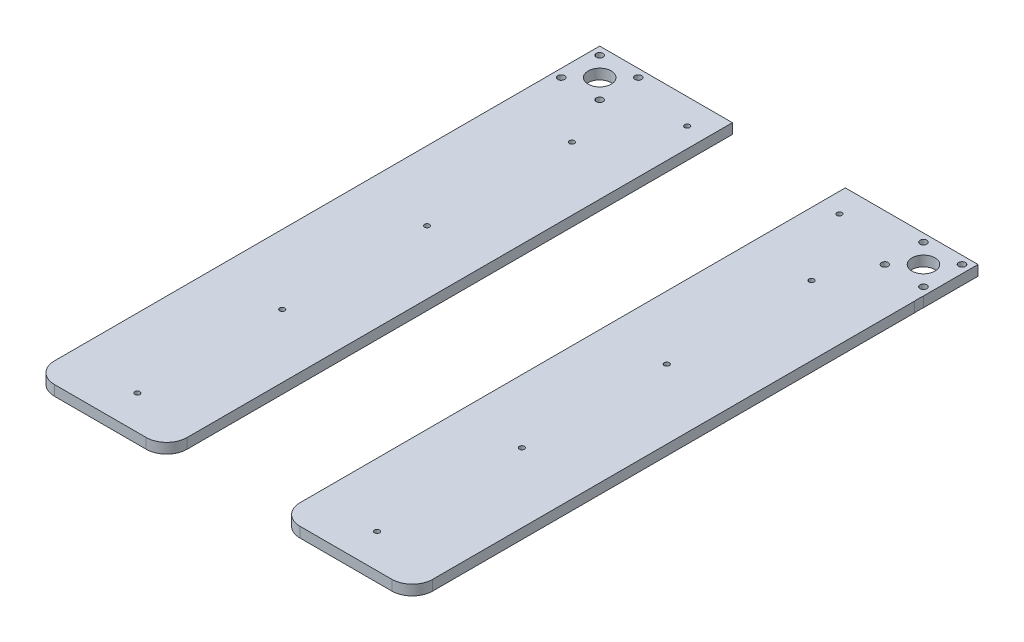
SolidWorks part; units mm, degrees
ref_plane "Alzado" through (0, 0, 0) normal (0, 0, 1) x (1, 0, 0)
ref_plane "Planta" through (0, 0, 0) normal (0, 1, 0) x (1, 0, 0)
ref_plane "Vista lateral" through (0, 0, 0) normal (1, 0, 0) x (0, 0, -1)
sketch "Croquis1" plane through (0, 0, 0) normal (0, 1, 0) x (1, 0, 0)
  line L0 (106.9678, 164.1099) -> (29.105, 164.1099)
  line L1 (-115.0322, 164.1099) -> (-115.0322, 132.1099)
  line L2 (41.105, -167.8901) -> (94.9678, -167.8901)
  line L3 (-103.0322, -167.8901) -> (-49.1693, -167.8901)
  line L4 (-37.1693, 164.1099) -> (-115.0322, 164.1099)
  line L5 (106.9678, 164.1099) -> (106.9678, 132.1099)
  line L6 (-115.0322, 164.1099) -> (-115.0322, -155.8901)
  line L7 (-37.1693, 164.1099) -> (-37.1693, -155.8901)
  line L8 (29.105, 164.1099) -> (29.105, -155.8901)
  line L9 (106.9678, 164.1099) -> (106.9678, -155.8901)
  circle A0 centre (-48.6966, 149.1099) radius 1.5
  circle A1 centre (40.6322, 149.1099) radius 1.5
  circle A2 centre (-99.0322, 148.1099) radius 6.75
  circle A3 centre (-87.7185, 136.7962) radius 2
  circle A4 centre (-110.3459, 136.7962) radius 2
  circle A5 centre (-110.3459, 159.4236) radius 2
  circle A6 centre (-87.7185, 159.4236) radius 2
  circle A7 centre (79.6541, 136.7962) radius 2
  circle A8 centre (102.2815, 136.7962) radius 2
  circle A9 centre (102.2815, 159.4236) radius 2
  circle A10 centre (79.6541, 159.4236) radius 2
  circle A12 centre (66.3, 107.1099) radius 1.5
  arc A13 (94.9678, -167.8901) -> (106.9678, -155.8901) centre (94.9678, -155.8901) ccw
  arc A14 (41.105, -167.8901) -> (29.105, -155.8901) centre (41.105, -155.8901) cw
  circle A15 centre (66.3, 22.1099) radius 1.5
  circle A16 centre (66.3, -62.8901) radius 1.5
  circle A17 centre (66.3, -147.8901) radius 1.5
  arc A19 (-37.1693, -155.8901) -> (-49.1693, -167.8901) centre (-49.1693, -155.8901) cw
  arc A20 (-103.0322, -167.8901) -> (-115.0322, -155.8901) centre (-103.0322, -155.8901) cw
  circle A21 centre (90.9678, 148.1099) radius 6.75
  arc A22 (-115.0322, 126.7276) -> (-115.0322, 132.1099) centre (-162.975, 129.4188) ccw
  arc A23 (106.9678, 132.1099) -> (106.9678, 126.7276) centre (154.9106, 129.4188) ccw
  circle A24 centre (-74.3644, 22.1099) radius 1.5
  circle A26 centre (-74.3644, 107.1099) radius 1.5
  circle A27 centre (-74.3644, -147.8901) radius 1.5
  circle A29 centre (-74.3644, -62.8901) radius 1.5
  dimension "D1" = 12
extrude "Saliente-Extruir1" add sketch "Croquis1" along normal blind 6
